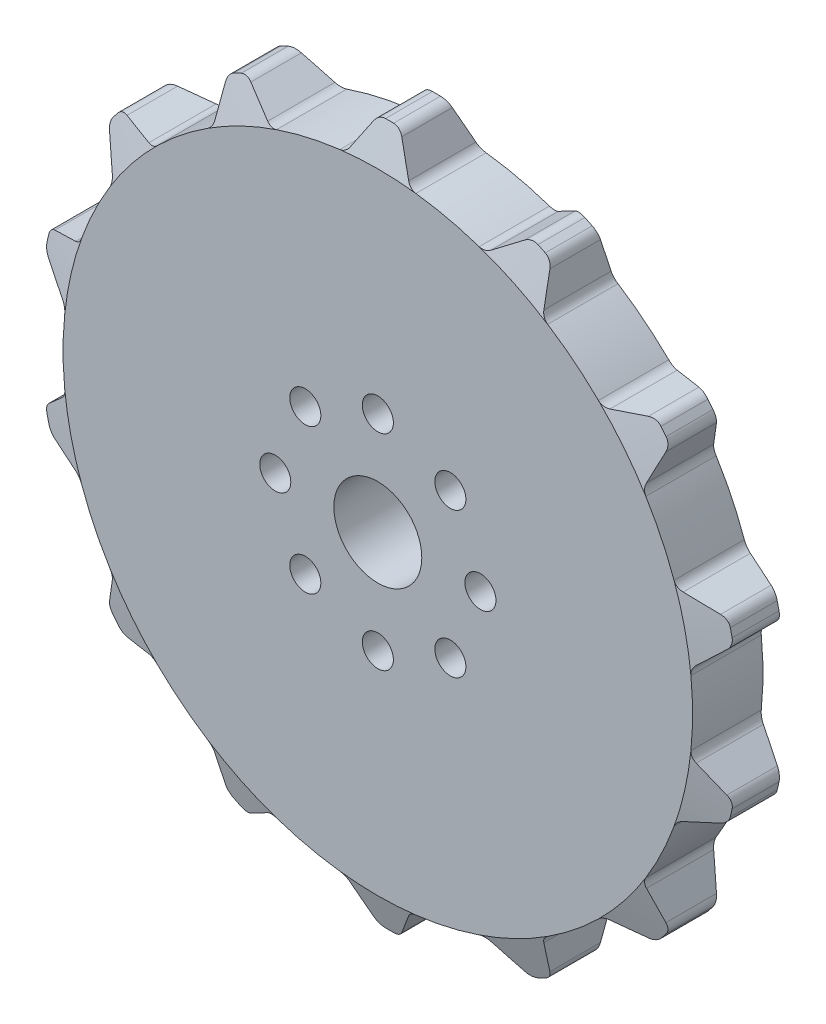
SolidWorks part; units mm, degrees
material "ABS"
ref_plane "Front" through (0, 0, 0) normal (0, 0, 1) x (1, 0, 0)
ref_plane "Top" through (0, 0, 0) normal (0, 1, 0) x (1, 0, 0)
ref_plane "Right" through (0, 0, 0) normal (1, 0, 0) x (0, 0, -1)
ref_axis "CL" through (0, 0, -5.5) along (0, 0, 1)
sketch "Sketch1" plane through (0, 0, 0) normal (0, 0, 1) x (1, 0, 0)
  circle A0 centre (0, 0) radius 53.7043
  circle A1 centre (0, 0) radius 55.7043 construction
  dimension "D1" = 111.4086
  dimension "D2" = 2
extrude "Main Body" add sketch "Sketch1" along normal mid plane 12
sketch "Sketch2" plane through (0, 0, -6) normal (0, 0, -1) x (-1, 0, 0)
  line L0 (5.5, -53.4219) -> (1.8372, -59.766)
  line L2 (-1.8372, -59.766) -> (-5.5, -53.4219)
  line L3 (0, -59.7943) -> (0, -53.7043) construction
  circle A0 centre (0, 0) radius 53.7043 construction
  arc A1 (5.5, -53.4219) -> (-5.5, -53.4219) centre (0, 0) cw
  arc A2 (-1.8372, -59.766) -> (1.8372, -59.766) centre (0, 0) ccw
  point P10 (0, -53.7043)
  circle M6 centre (0, 0) radius 53.7043
  dimension "D1" = 11
  dimension "D2" = 60
  dimension "D3" = 6.09
extrude "Track Tooth" add sketch "Sketch2" against normal up to surface (12 mm away) contours L3 A2 L0 A1 | A2 L3 L2 M6 up to face at (53.7043, 0, 6)
fillet "Fillet5" radius 2 4 edges at (5.5, -53.4219, 0) (-5.5, -53.4219, 0) (1.8372, -59.766, 0) (-1.8372, -59.766, 0)
pattern_circular "CirPattern4" count 14 over 360 about axis through (0, 0, 0) along (0, 0, 1) of "Track Tooth", "Fillet5"
sketch "Sketch3" plane through (0, 0, 0) normal (1, 0, 0) x (0, 0, -1)
  line L0 (-6, -59.7943) -> (-4, -59.7943)
  line L1 (-4, -59.7943) -> (-6, -53.7043)
  line L2 (-6, -53.7043) -> (-6, -59.7943)
  line L3 (-6, -50.8457) -> (-6, -53.3112) construction
  line L4 (-6, -53.4219) -> (-6, -53.7043) construction
  line L6 (6, -58.7904) -> (6, -54.2966) construction
  line L8 (0, 0) -> (0, -59.7943) construction
  line L9 (-6, -59.7943) -> (6, -59.7943) construction
  line L10 (4, -59.7943) -> (6, -59.7943)
  line L11 (6, -59.7943) -> (6, -53.7043)
  line L12 (6, -53.7043) -> (4, -59.7943)
  dimension "D1" = 2
  dimension "D2" = 6.09
revolve "Cut-Revolve3" cut sketch "Sketch3" angle 360 about axis through (0, 0, -5.5) along (0, 0, 1)
sketch "Sketch5" plane through (0, 0, -6) normal (0, 0, -1) x (-1, 0, 0)
  circle A0 centre (0, 0) radius 7.5
  dimension "D1" = 15
extrude "Cut-Extrude1" cut sketch "Sketch5" against normal up to next
hole_wizard "M5 Clearance Hole1" positions "Sketch7" profile "Sketch8" hole size "M5" standard "ANSI Metric" end condition up to next
sketch "Sketch7" plane through (0, 0, 6) normal (0, 0, -1) x (-1, 0, 0)
  line L0 (0, 0) -> (17.5, 0) construction
  circle A0 centre (0, 0) radius 17.5 construction
  point P0 (17.5, 0)
  dimension "D1" = 35
sketch "Sketch8" plane through (-17.5, 0, 6) normal (1, 0, 0) x (0, -1, 0)
  line L0 (0, 0) -> (0, 12.001)
  line L1 (0, 12.001) -> (2.65, 12.001)
  line L2 (2.65, 12.001) -> (2.65, 0)
  line L5 (2.65, 0) -> (0, 0)
  line L11 (0, -6.35) -> (0, 107.95) construction
  dimension "Thru Hole Dia." = 5.3
  dimension "Thru Hole Depth" = 12.001
pattern_circular "CirPattern9" count 8 over 360 about axis through (0, 0, 0) along (0, 0, 1) of "M5 Clearance Hole1"
equation "\"Pitch\"= 25mm"
equation "\"Num_Teeth\"= 14"
equation "\"Pitch_Diameter\"= \"Pitch\" * \"Num_Teeth\" / 3.14159"
equation "\"D1@Sketch1\"= \"Pitch_Diameter\""
equation "\"Track_Bend_MidLine\"= 2mm"
equation "\"D2@Sketch1\"= \"Track_Bend_MidLine\""
equation "\"D1@CirPattern4\"=\"Num_Teeth\""
